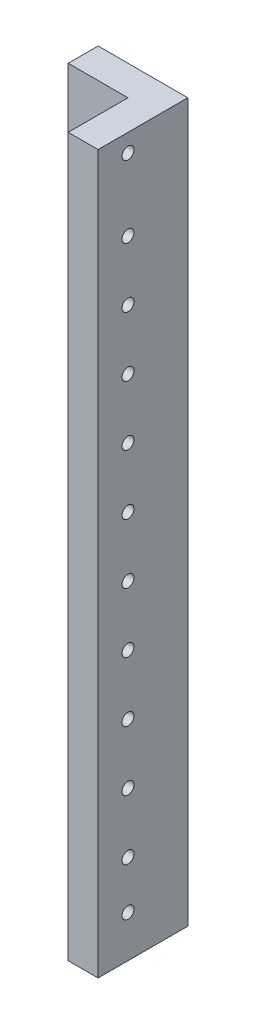
SolidWorks part; units mm, degrees
ref_plane "Front Plane" through (0, 0, 0) normal (0, 0, 1) x (1, 0, 0)
ref_plane "Top Plane" through (0, 0, 0) normal (0, 1, 0) x (1, 0, 0)
ref_plane "Right Plane" through (0, 0, 0) normal (1, 0, 0) x (0, 0, -1)
sketch "Sketch1" plane through (0, 0, 0) normal (0, 1, 0) x (1, 0, 0)
  line L0 (-19.6615, 6.6071) -> (-4.6615, 6.6071)
  line L1 (-4.6615, 6.6071) -> (-4.6615, -8.3929)
  line L2 (-19.6615, 6.6071) -> (-19.6615, 1.6071)
  line L3 (-4.6615, -8.3929) -> (-9.6615, -8.3929)
  line L4 (-19.6615, 1.6071) -> (-9.6615, 1.6071)
  line L5 (-9.6615, 1.6071) -> (-9.6615, -8.3929)
  dimension "D1" = 15
  dimension "D2" = 15
  dimension "D3" = 5
  dimension "D4" = 5
extrude "Boss-Extrude1" add sketch "Sketch1" along normal blind 120
sketch "Sketch2" plane through (-4.6615, 0, 0) normal (1, 0, 0) x (0, 0, -1)
  line L0 (-8.3929, 120) -> (6.6071, 120) construction
  line L1 (-8.3929, 120) -> (-8.3929, 0) construction
  circle A0 centre (-3.3929, 117) radius 1
  dimension "D3" = 2
  dimension "D1" = 3
  dimension "D2" = 5
extrude "Cut-Extrude3" cut sketch "Sketch2" against normal blind 120
sketch "Sketch4" plane through (0, 0, -6.6071) normal (0, 0, -1) x (-1, 0, 0)
  line L0 (19.6615, 120) -> (19.6615, 0) construction
  line L2 (4.6615, 120) -> (19.6615, 120) construction
  circle A0 centre (14.6615, 113) radius 1
  dimension "D3" = 2
  dimension "D1" = 5
  dimension "D2" = 7
extrude "Cut-Extrude4" cut sketch "Sketch4" against normal blind 120
sketch "Sketch5" plane through (-4.6615, 0, 0) normal (1, 0, 0) x (0, 0, -1)
  line L0 (-8.3929, 120) -> (-8.3929, 0) construction
  line L1 (-8.3929, 0) -> (6.6071, 0) construction
  circle A0 centre (-3.3929, 7) radius 1
  dimension "D3" = 2
  dimension "D1" = 5
  dimension "D2" = 7
extrude "Cut-Extrude5" cut sketch "Sketch5" against normal blind 120
sketch "Sketch6" plane through (0, 0, -6.6071) normal (0, 0, -1) x (-1, 0, 0)
  line L0 (19.6615, 120) -> (19.6615, 0) construction
  line L1 (4.6615, 0) -> (19.6615, 0) construction
  circle A0 centre (14.6615, 3) radius 1
  dimension "D3" = 2
  dimension "D1" = 5
  dimension "D2" = 3
extrude "Cut-Extrude6" cut sketch "Sketch6" against normal blind 120
sketch "Sketch8" plane through (-4.6615, 0, 0) normal (1, 0, 0) x (0, 0, -1)
  line L0 (-8.3929, 120) -> (-8.3929, 110) construction
  line L1 (-8.3929, 120) -> (-8.3929, 0) construction
  line L2 (-8.3929, 110) -> (14.167, 110) construction
  line L3 (-3.3929, 117) -> (-3.3929, 7) construction
  circle A0 centre (-3.3929, 105) radius 1
  circle A1 centre (-3.3929, 95) radius 1
  circle A2 centre (-3.3929, 85) radius 1
  circle A3 centre (-3.3929, 75) radius 1
  circle A4 centre (-3.3929, 65) radius 1
  circle A5 centre (-3.3929, 55) radius 1
  circle A6 centre (-3.3929, 45) radius 1
  circle A7 centre (-3.3929, 35) radius 1
  circle A8 centre (-3.3929, 25) radius 1
  circle A9 centre (-3.3929, 15) radius 1
  dimension "D2" = 2
  dimension "D1" = 10
  dimension "D3" = 5
  dimension "D4" = 10
extrude "Cut-Extrude7" cut sketch "Sketch8" against normal blind 120
sketch "Sketch9" plane through (0, 0, -6.6071) normal (0, 0, -1) x (-1, 0, 0)
  line L0 (14.6615, 3) -> (14.6615, 113) construction
  line L1 (19.6615, 0) -> (19.6615, 10) construction
  line L2 (19.6615, 120) -> (19.6615, 0) construction
  line L3 (19.6615, 10) -> (10.6024, 10) construction
  circle A0 centre (14.6615, 15) radius 1
  circle A1 centre (14.6615, 25) radius 1
  circle A2 centre (14.6615, 35) radius 1
  circle A3 centre (14.6615, 45) radius 1
  circle A4 centre (14.6615, 55) radius 1
  circle A5 centre (14.6615, 65) radius 1
  circle A6 centre (14.6615, 75) radius 1
  circle A7 centre (14.6615, 85) radius 1
  circle A8 centre (14.6615, 95) radius 1
  circle A9 centre (14.6615, 105) radius 1
  dimension "D2" = 2
  dimension "D1" = 10
  dimension "D3" = 5
  dimension "D4" = 10
extrude "Cut-Extrude8" cut sketch "Sketch9" against normal blind 120
